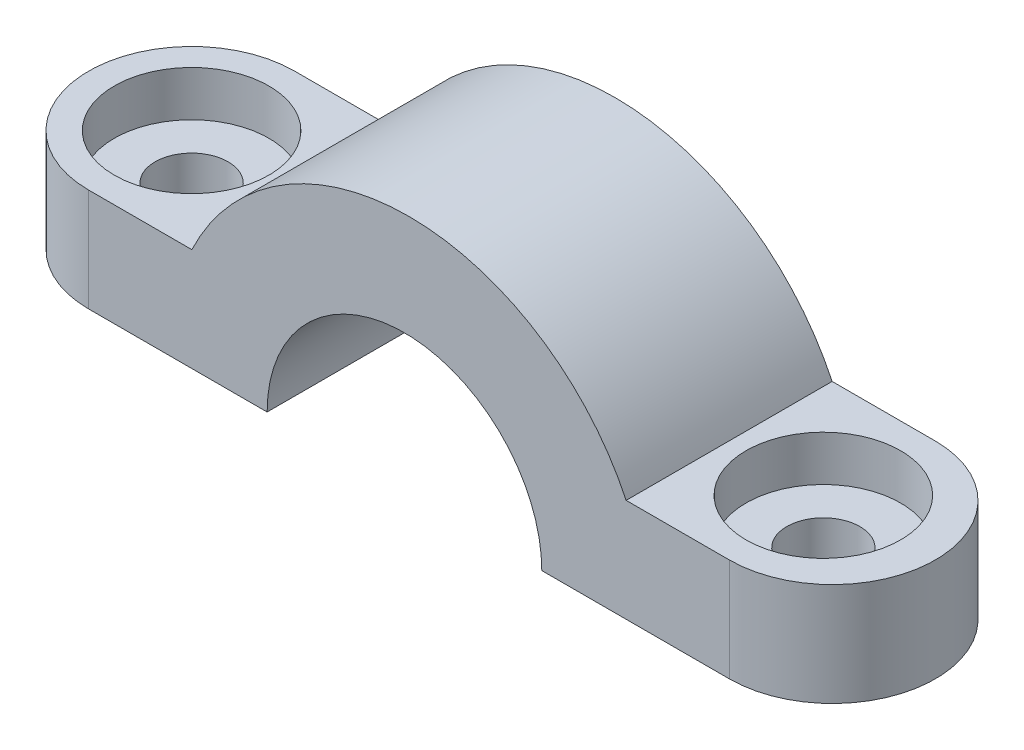
SolidWorks part; units mm, degrees
material "Plain Carbon Steel"
ref_plane "Front Plane" through (0, 0, 0) normal (0, 0, 1) x (1, 0, 0)
ref_plane "Top Plane" through (0, 0, 0) normal (0, 1, 0) x (1, 0, 0)
ref_plane "Right Plane" through (0, 0, 0) normal (1, 0, 0) x (0, 0, -1)
sketch "Sketch1" plane through (0, 0, 0) normal (0, 1, 0) x (1, 0, 0)
  line L0 (-29.21, 0) -> (30.0479, 0) construction
  line L1 (-29.21, 9.525) -> (30.0479, 9.525)
  line L2 (-29.21, -9.525) -> (30.0479, -9.525)
  arc A0 (-29.21, 9.525) -> (-29.21, -9.525) centre (-29.21, 0) ccw
  arc A1 (30.0479, -9.525) -> (30.0479, 9.525) centre (30.0479, 0) ccw
  point P3 (0.419, 0)
  dimension "D1" = 19.05
  dimension "D2" = 29.21
extrude "Base Extrude" add sketch "Sketch1" along normal blind 9.525
sketch "Sketch2" plane through (0, 0, 9.525) normal (0, 0, 1) x (1, 0, 0)
  line L0 (-29.21, 0) -> (30.0479, 0) construction
  circle A0 centre (0.419, 0) radius 22.225
  line M2 (-29.21, 0) -> (30.0479, 0)
  line M4 (30.0479, 9.525) -> (-29.21, 9.525)
extrude "Arch Extrude" add sketch "Sketch2" against normal up to surface (19.05 mm away) contours A0 M2 M4 | A0 M4 up to face at (0.419, 4.7625, -9.525)
sketch "Sketch3" plane through (0, 0, 9.525) normal (0, 0, 1) x (1, 0, 0)
  circle A0 centre (0, 0) radius 12.7
extrude "Arch Cut" cut sketch "Sketch3" against normal through all
sketch "Sketch4" plane through (0, 9.525, 0) normal (0, 1, 0) x (1, 0, 0)
  circle A0 centre (-29.21, 0) radius 7.1501
  point P0 (-29.21, 0)
  point P1 (30.0479, 0)
extrude "Large Cut" cut sketch "Sketch4" against normal blind 4.191
sketch "Sketch5" plane through (0, 5.334, 0) normal (0, 1, 0) x (1, 0, 0)
  circle A0 centre (-29.21, 0) radius 3.3782
extrude "Small Cut" cut sketch "Sketch5" against normal through all
mirror "Mirror" about plane through (0, 0, 0) normal (1, 0, 0) of "Large Cut", "Small Cut"
